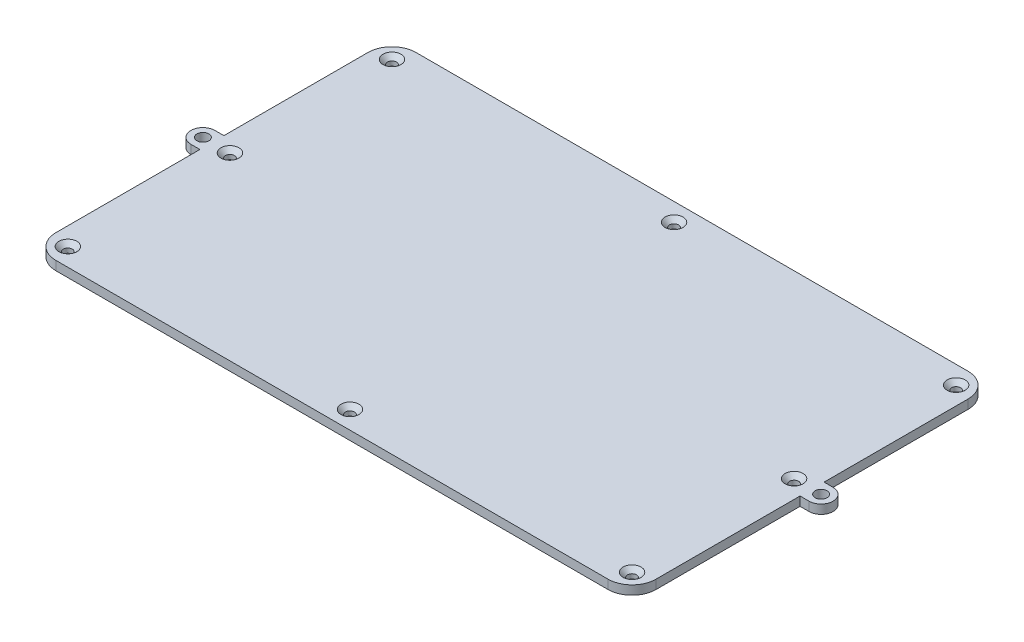
SolidWorks part; units mm, degrees
ref_plane "Front Plane" through (0, 0, 0) normal (0, 0, 1) x (1, 0, 0)
ref_plane "Top Plane" through (0, 0, 0) normal (0, 1, 0) x (1, 0, 0)
ref_plane "Right Plane" through (0, 0, 0) normal (1, 0, 0) x (0, 0, -1)
sketch "Sketch1" plane through (0, 0, 0) normal (0, 1, 0) x (1, 0, 0)
  line L1 (-100, -60) -> (100, -60)
  line L2 (-100, -60) -> (-100, 60)
  line L3 (-100, 60) -> (100, 60)
  line L4 (100, -60) -> (100, 60)
  line L5 (-100, -60) -> (100, 60) construction
  line L6 (-100, 60) -> (100, -60) construction
  point P0 (0, 0)
  dimension "D1" = 200
  dimension "D2" = 120
extrude "Boss-Extrude1" add sketch "Sketch1" along normal blind 3
sketch "Sketch2" plane through (0, 3, 0) normal (0, 1, 0) x (1, 0, 0)
  line L0 (100, 60) -> (-100, 60) construction
  line L1 (-100, 60) -> (-100, -60) construction
  line L2 (-100, -60) -> (100, -60) construction
  line L3 (100, -60) -> (100, 60) construction
  point P0 (-94, 54)
  point P1 (0, 54)
  point P2 (94, 54)
  point P3 (94, 0)
  point P4 (94, -54)
  point P5 (0, -54)
  point P6 (-94, -54)
  point P7 (-94, 0)
  dimension "D1" = 6
  dimension "D2" = 6
  dimension "D3" = 6
  dimension "D4" = 6
hole_wizard "CSK for M3 Flat Head Machine Screw1" positions "Sketch5" profile "Sketch6" countersink size "M3" standard "ANSI Metric" end condition through all
sketch "Sketch5" plane through (0, 3, 0) normal (0, 1, 0) x (1, 0, 0)
  point P0 (-94, 54)
  point P3 (0, 54)
  point P6 (94, 54)
  point P9 (94, 0)
  point P12 (94, -54)
  point P15 (0, -54)
  point P18 (-94, -54)
  point P21 (-94, 0)
sketch "Sketch6" plane through (-94, 3, -54) normal (1, 0, 0) x (0, 0, 1)
  line L0 (0, 0) -> (0, 3)
  line L1 (0, 3) -> (1.5, 3)
  line L2 (1.5, 3) -> (1.5, 1.5)
  line L3 (1.5, 1.5) -> (3, 0)
  line L5 (3, 0) -> (0, 0)
  line L6 (-1.5, 1.5) -> (-3, 0) construction
  line L11 (0, -6.35) -> (0, 107.95) construction
  dimension "Thru Hole Dia." = 3
  dimension "Thru Hole Depth" = 3
  dimension "Near C'Sink Dia." = 6
  dimension "Near C'Sink Angle" = 90
fillet "Fillet1" radius 8 4 edges at (100, 1.5, 60) (100, 1.5, -60) (-100, 1.5, 60) (-100, 1.5, -60)
sketch "Sketch7" plane through (0, 0, 0) normal (0, -1, 0) x (1, 0, 0)
  line L0 (100, 4) -> (103, 4)
  line L1 (100, 52) -> (100, -52) construction
  line L2 (103, -4) -> (100, -4)
  line L3 (100, 4) -> (100, -4)
  line L4 (-100, -4) -> (-103, -4)
  line L5 (-100, -52) -> (-100, 52) construction
  line L6 (-103, 4) -> (-100, 4)
  line L7 (-100, 4) -> (-100, -4)
  arc A0 (103, 4) -> (103, -4) centre (103, 0) cw
  arc A1 (-103, -4) -> (-103, 4) centre (-103, 0) cw
  dimension "D2" = 4
  dimension "D1" = 8
  dimension "D3" = 3
  dimension "D4" = 8
  dimension "D5" = 3
extrude "Boss-Extrude2" add sketch "Sketch7" against normal blind 3
sketch "Sketch9" plane through (0, 3, 0) normal (0, 1, 0) x (1, 0, 0)
  circle A0 centre (-103, 0) radius 2
  circle A1 centre (103, 0) radius 2
  dimension "D1" = 4
  dimension "D2" = 4
extrude "Cut-Extrude1" cut sketch "Sketch9" against normal blind 4
equation "\"D1@Sketch2\"=\"D2@Sketch2\""
equation "\"D3@Sketch2\"=\"D2@Sketch2\""
equation "\"D4@Sketch2\"=\"D2@Sketch2\""
